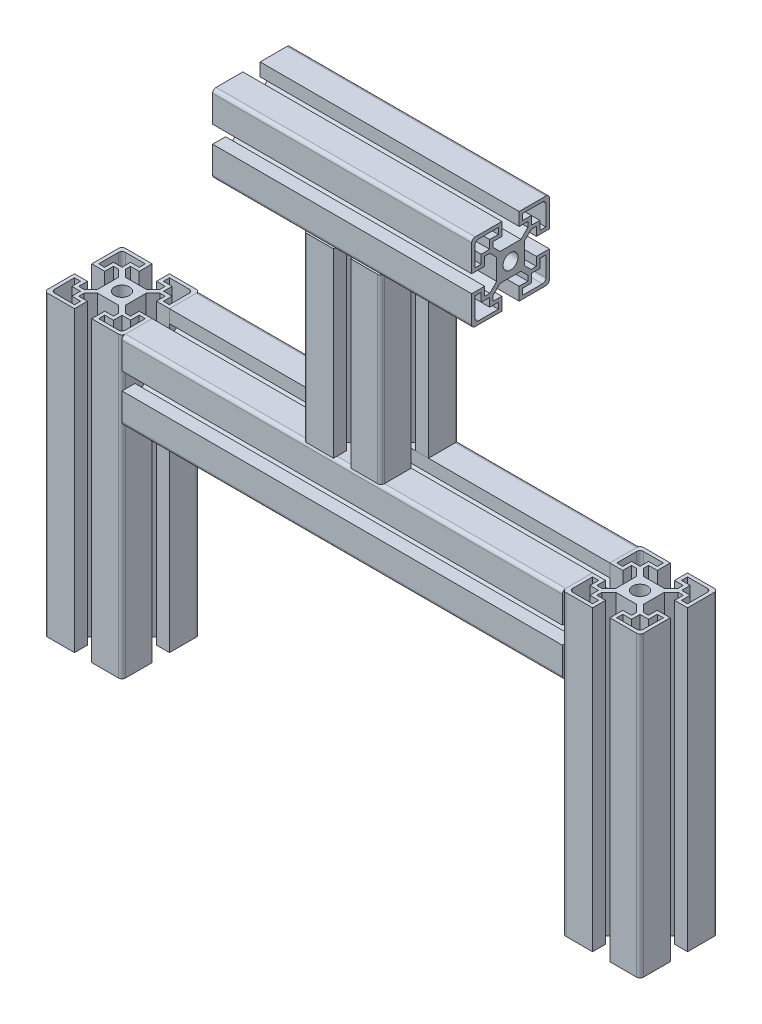
SolidWorks part; units mm, degrees
ref_plane "Front Plane" through (0, 0, 0) normal (0, 0, 1) x (1, 0, 0)
ref_plane "Top Plane" through (0, 0, 0) normal (0, 1, 0) x (1, 0, 0)
ref_plane "Right Plane" through (0, 0, 0) normal (1, 0, 0) x (0, 0, -1)
sketch "Sketch1" plane through (0, 0, 0) normal (0, 0, 1) x (1, 0, 0)
  line L0 (-142.4658, -81.2785) -> (-142.4658, 68.7215)
  line L1 (-142.4658, 68.7215) -> (157.5342, 68.7215)
  line L2 (157.5342, 68.7215) -> (157.5342, -81.2785)
  line L3 (7.5342, 68.7215) -> (7.5342, 218.7215)
  line L4 (-67.4658, 218.7215) -> (82.5342, 218.7215)
  point P8 (7.5342, 218.7215)
  dimension "D1" = 300
  dimension "D2" = 150
other "Perfil aluminio 45 X 45(1)"
ref_plane "Plane2" through (157.5342, 68.7215, 0) normal (0, -1, 0) x (1, 0, 0)
sketch "Sketch16" plane through (157.5342, 68.7215, 0) normal (0, -1, 0) x (1, 0, 0)
  line L0 (22.5, -22.5) -> (-22.5, 22.5) construction
  line L1 (-20.5, 22.5) -> (-5, 22.5)
  line L2 (-22.5, 20.5) -> (-22.5, 5)
  line L3 (-20.5, -22.5) -> (-5, -22.5)
  line L4 (22.5, 20.5) -> (22.5, 5)
  line L5 (0, -8) -> (0, 22.5) construction
  line L6 (8, 0) -> (-22.5, 0) construction
  line L7 (-5, 22.5) -> (-5, 14.9829)
  line L8 (-5, 14.9829) -> (-10.05, 14.9829)
  line L9 (-10.05, 14.9829) -> (-10.05, 11.9902)
  line L10 (-10.05, 11.9902) -> (-6.0598, 8)
  line L11 (-6.0598, 8) -> (6.0598, 8)
  line L12 (22.5, -5) -> (22.5, -20.5)
  line L13 (10.05, 11.9902) -> (6.0598, 8)
  line L14 (10.05, 14.9829) -> (10.05, 11.9902)
  line L15 (5, 14.9829) -> (10.05, 14.9829)
  line L16 (5, 22.5) -> (5, 14.9829)
  line L17 (-22.5, -5) -> (-14.9829, -5)
  line L18 (-14.9829, -5) -> (-14.9829, -10.05)
  line L19 (-14.9829, -10.05) -> (-11.9902, -10.05)
  line L20 (-11.9902, -10.05) -> (-8, -6.0598)
  line L21 (-22.5, -5) -> (-22.5, -20.5)
  line L22 (-8, 6.0598) -> (-8, -6.0598)
  line L23 (-11.9902, 10.05) -> (-8, 6.0598)
  line L24 (-14.9829, 10.05) -> (-11.9902, 10.05)
  line L25 (-14.9829, 5) -> (-14.9829, 10.05)
  line L26 (-22.5, 5) -> (-14.9829, 5)
  line L27 (22.5, 5) -> (14.9829, 5)
  line L28 (14.9829, 5) -> (14.9829, 10.05)
  line L29 (14.9829, 10.05) -> (11.9902, 10.05)
  line L30 (11.9902, 10.05) -> (8, 6.0598)
  line L31 (8, 6.0598) -> (8, -6.0598)
  line L32 (5, -22.5) -> (20.5, -22.5)
  line L33 (11.9902, -10.05) -> (8, -6.0598)
  line L34 (14.9829, -10.05) -> (11.9902, -10.05)
  line L35 (14.9829, -5) -> (14.9829, -10.05)
  line L36 (22.5, -5) -> (14.9829, -5)
  line L37 (5, -22.5) -> (5, -14.9829)
  line L38 (5, -14.9829) -> (10.05, -14.9829)
  line L39 (10.05, -14.9829) -> (10.05, -11.9902)
  line L40 (10.05, -11.9902) -> (6.0598, -8)
  line L41 (12.05, 16.9829) -> (12.05, 12.05)
  line L42 (-6.0598, -8) -> (6.0598, -8)
  line L43 (-10.05, -11.9902) -> (-6.0598, -8)
  line L44 (-10.05, -14.9829) -> (-10.05, -11.9902)
  line L45 (-5, -14.9829) -> (-10.05, -14.9829)
  line L46 (-5, -22.5) -> (-5, -14.9829)
  line L47 (5, 22.5) -> (20.5, 22.5)
  line L48 (7, 16.9829) -> (12.05, 16.9829)
  line L49 (7, 20.5) -> (7, 16.9829)
  line L50 (7, 20.5) -> (18.5, 20.5)
  line L51 (20.5, 18.5) -> (20.5, 7)
  line L52 (20.5, 7) -> (16.9829, 7)
  line L53 (16.9829, 7) -> (16.9829, 12.05)
  line L54 (16.9829, 12.05) -> (12.05, 12.05)
  line L55 (-20.5, 18.5) -> (-20.5, 7)
  line L56 (-7, 20.5) -> (-18.5, 20.5)
  line L57 (-7, 20.5) -> (-7, 16.9829)
  line L58 (-7, 16.9829) -> (-12.05, 16.9829)
  line L59 (-12.05, 16.9829) -> (-12.05, 12.05)
  line L60 (-16.9829, 12.05) -> (-12.05, 12.05)
  line L61 (-16.9829, 7) -> (-16.9829, 12.05)
  line L62 (-20.5, 7) -> (-16.9829, 7)
  line L63 (12.05, -16.9829) -> (12.05, -12.05)
  line L64 (16.9829, -12.05) -> (12.05, -12.05)
  line L65 (16.9829, -7) -> (16.9829, -12.05)
  line L66 (20.5, -7) -> (16.9829, -7)
  line L67 (20.5, -18.5) -> (20.5, -7)
  line L68 (7, -20.5) -> (18.5, -20.5)
  line L69 (7, -20.5) -> (7, -16.9829)
  line L70 (7, -16.9829) -> (12.05, -16.9829)
  line L71 (-20.5, -18.5) -> (-20.5, -7)
  line L72 (-7, -20.5) -> (-18.5, -20.5)
  line L73 (-7, -20.5) -> (-7, -16.9829)
  line L74 (-7, -16.9829) -> (-12.05, -16.9829)
  line L75 (-12.05, -16.9829) -> (-12.05, -12.05)
  line L76 (-16.9829, -12.05) -> (-12.05, -12.05)
  line L77 (-16.9829, -7) -> (-16.9829, -12.05)
  line L78 (-20.5, -7) -> (-16.9829, -7)
  circle A0 centre (0, 0) radius 4.3563
  arc A1 (18.5, -20.5) -> (20.5, -18.5) centre (18.5, -18.5) ccw
  arc A2 (22.5, -20.5) -> (20.5, -22.5) centre (20.5, -20.5) cw
  arc A3 (-22.5, -20.5) -> (-20.5, -22.5) centre (-20.5, -20.5) ccw
  arc A4 (-18.5, -20.5) -> (-20.5, -18.5) centre (-18.5, -18.5) cw
  arc A5 (-22.5, 20.5) -> (-20.5, 22.5) centre (-20.5, 20.5) cw
  arc A6 (-20.5, 18.5) -> (-18.5, 20.5) centre (-18.5, 18.5) cw
  arc A7 (18.5, 20.5) -> (20.5, 18.5) centre (18.5, 18.5) cw
  arc A8 (22.5, 20.5) -> (20.5, 22.5) centre (20.5, 20.5) ccw
  point P6 (22.5, 22.5)
  point P16 (0, 22.5)
  point P17 (0, 8)
  point P30 (-8, 0)
  point P31 (-22.5, 0)
  point P43 (22.5, 0)
  point P44 (8, 0)
  point P55 (0, -8)
  point P56 (0, -22.5)
  point P92 (20.5, -20.5)
  point P100 (-20.5, -20.5)
  point P106 (-20.5, 20.5)
  point P109 (20.5, 20.5)
  point P112 (22.5, 22.5)
  point P113 (-22.5, 22.5)
  point P114 (-22.5, -22.5)
  point P115 (22.5, -22.5)
  point P116 (0, 0)
  dimension "D1" = 45
  dimension "D2" = 45
  dimension "D3" = 5
  dimension "D4" = 14.5
  dimension "D5" = 10.05
  dimension "D6" = 135
  dimension "D7" = 2
